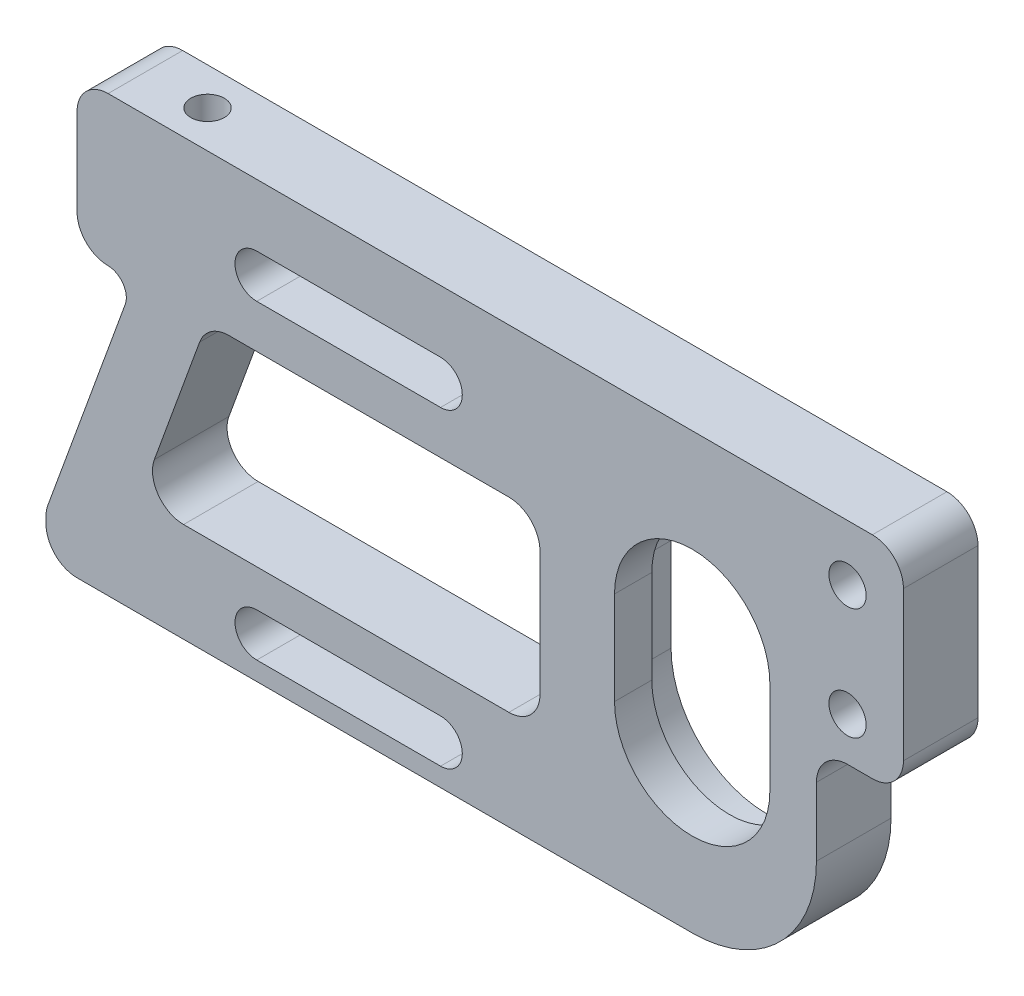
SolidWorks part; units mm, degrees
ref_plane "Front Plane" through (0, 0, 0) normal (0, 0, 1) x (1, 0, 0)
ref_plane "Top Plane" through (0, 0, 0) normal (0, 1, 0) x (1, 0, 0)
ref_plane "Right Plane" through (0, 0, 0) normal (1, 0, 0) x (0, 0, -1)
sketch "Sketch1" plane through (0, 0, 0) normal (0, 0, 1) x (1, 0, 0)
  line L0 (10, 40.8445) -> (10, -9.5059) construction
  line L1 (2.5, 35) -> (69, 35)
  line L2 (0, 3.4748) -> (0, 0)
  line L3 (0, 0) -> (62, 0)
  line L4 (69, 35) -> (69, 18)
  line L5 (52, 20.5) -> (52, 13) construction
  line L6 (58.25, 20.5) -> (58.25, 13)
  line L7 (45.75, 20.5) -> (45.75, 13)
  line L8 (69, 18) -> (62, 18)
  line L9 (62, 18) -> (62, 0)
  line L10 (7.5, 8) -> (39.75, 8)
  line L11 (12.9596, 23) -> (39.75, 23)
  line L12 (12.9596, 23) -> (7.5, 8)
  line L13 (7.1066, 23) -> (0, 3.4748)
  line L14 (7.7912, 24.8811) -> (2.3317, 9.8811) construction
  line L15 (7.1066, 23) -> (2.5, 23)
  line L16 (2.5, 23) -> (2.5, 35)
  line L17 (39.75, 23) -> (39.75, 8)
  line L18 (16.9596, 28.25) -> (31.75, 28.25) construction
  line L19 (16.9596, 30) -> (31.75, 30)
  line L20 (16.9596, 26.5) -> (31.75, 26.5)
  line L21 (12.9596, 15.75) -> (37.1976, 15.75) construction
  line L22 (16.9596, 3.25) -> (31.75, 3.25) construction
  line L23 (16.9596, 1.5) -> (31.75, 1.5)
  line L24 (16.9596, 5) -> (31.75, 5)
  arc A0 (58.25, 20.5) -> (45.75, 20.5) centre (52, 20.5) ccw
  arc A1 (45.75, 13) -> (58.25, 13) centre (52, 13) ccw
  circle A2 centre (64.5, 30.5) radius 1.5
  circle A3 centre (64.5, 21.5) radius 1.5
  arc A4 (16.9596, 30) -> (16.9596, 26.5) centre (16.9596, 28.25) ccw
  arc A5 (31.75, 26.5) -> (31.75, 30) centre (31.75, 28.25) ccw
  arc A6 (16.9596, 1.5) -> (16.9596, 5) centre (16.9596, 3.25) cw
  arc A7 (31.75, 5) -> (31.75, 1.5) centre (31.75, 3.25) cw
  point P8 (52, 16.75)
  point P30 (24.3548, 28.25)
  point P39 (24.3548, 3.25)
  dimension "D8" = 3
  dimension "D9" = 3
  dimension "D12" = 9
  dimension "D3" = 10
  dimension "D4" = 42
  dimension "D5" = 12.5
  dimension "D6" = 7.5
  dimension "D7" = 13
  dimension "D10" = 4.5
  dimension "D11" = 4.5
  dimension "D13" = 17
  dimension "D14" = 7
  dimension "D15" = 35
  dimension "D16" = 8
  dimension "D17" = 12
  dimension "D18" = 7.5
  dimension "D19" = 6
  dimension "D20" = 70
  dimension "D21" = 5.5
  dimension "D22" = 7.5
  dimension "D23" = 69
  dimension "D24" = 3.5
  dimension "D25" = 3.5
  dimension "D26" = 4
  dimension "D27" = 8
  dimension "D28" = 12.5
extrude "Boss-Extrude1" add sketch "Sketch1" along normal blind 6
sketch "Sketch2" plane through (0, 0, 0) normal (0, 0, -1) x (-1, 0, 0)
  line L0 (-52, 20.5) -> (-52, 13) construction
  line L1 (-44.3, 20.5) -> (-44.3, 13)
  line L2 (-59.7, 20.5) -> (-59.7, 13)
  arc A0 (-44.3, 20.5) -> (-59.7, 20.5) centre (-52, 20.5) ccw
  arc A1 (-59.7, 13) -> (-44.3, 13) centre (-52, 13) ccw
  circle A2 centre (-64.5, 30.5) radius 3.25
  circle A3 centre (-64.5, 21.5) radius 3.25
  point P4 (-52, 16.75)
  dimension "D1" = 6.5
  dimension "D2" = 6.5
  dimension "D3" = 15.4
extrude "Cut-Extrude1" cut sketch "Sketch2" against normal blind 3
fillet "Fillet1" radius 2.5 11 edges at (0, 3.4748, 3) (0, 0, 3) (2.5, 23, 3) (2.5, 35, 3) (62, 18, 3) (69, 18, 3) (69, 35, 3) (39.75, 8, 3) (39.75, 23, 3) (7.5, 8, 3) (12.9596, 23, 3)
fillet "Fillet2" radius 1.5 1 edges at (7.1066, 23, 3)
fillet "Fillet3" radius 10 1 edges at (62, 0, 3)
sketch "Sketch3" plane through (0, 0, 0) normal (0, 0, -1) x (-1, 0, 0)
  line L0 (-31.75, 28.25) -> (-16.9596, 28.25) construction
  line L1 (-31.75, 31.75) -> (-16.9596, 31.75)
  line L2 (-31.75, 24.75) -> (-16.9596, 24.75)
  line L3 (-31.75, 3.25) -> (-16.9596, 3.25) construction
  line L4 (-31.75, 6.75) -> (-16.9596, 6.75)
  line L6 (-35.25, 3.25) -> (-35.25, 0)
  line L7 (-2.5, 0) -> (-52, 0) construction
  line L8 (-35.25, 0) -> (-13.4596, 0)
  line L9 (-13.4596, 0) -> (-13.4596, 3.25)
  arc A0 (-31.75, 31.75) -> (-31.75, 24.75) centre (-31.75, 28.25) ccw
  arc A1 (-16.9596, 24.75) -> (-16.9596, 31.75) centre (-16.9596, 28.25) ccw
  arc A2 (-31.75, 6.75) -> (-35.25, 3.25) centre (-31.75, 3.25) ccw
  arc A3 (-13.4596, 3.25) -> (-16.9596, 6.75) centre (-16.9596, 3.25) ccw
  point P4 (-24.3548, 28.25)
  point P9 (-24.3548, 3.6532)
  dimension "D2" = 3.5
  dimension "D3" = 3.5
  dimension "D1" = 7
  dimension "D4" = 3.5
extrude "Cut-Extrude2" cut sketch "Sketch3" against normal blind 2
sketch "Sketch4" plane through (0, 0, 0) normal (0, -1, 0) x (1, 0, 0)
  line L0 (0, 0) -> (0, 6) construction
  circle A0 centre (10, 3) radius 1.35
  circle A1 centre (45, 3) radius 1.35
  point P6 (0, 3)
  dimension "D3" = 2.7
  dimension "D4" = 2.7
  dimension "D1" = 10
  dimension "D2" = 35
extrude "Cut-Extrude3" cut sketch "Sketch4" against normal blind 7
sketch "Sketch5" plane through (0, 35, 0) normal (0, 1, 0) x (1, 0, 0)
  line L0 (0, -6) -> (0, 0) construction
  circle A0 centre (10, -3) radius 1.35
  point P4 (0, -3)
  dimension "D2" = 2.7
  dimension "D1" = 10
extrude "Cut-Extrude4" cut sketch "Sketch5" against normal blind 10
